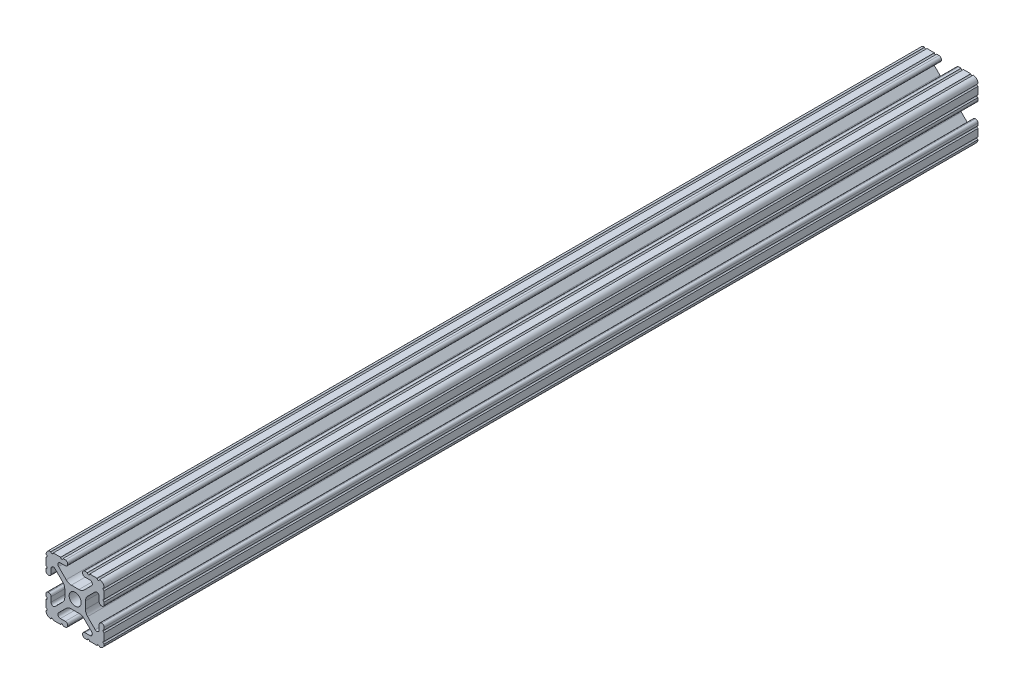
SolidWorks part; units mm, degrees
ref_plane "Front Plane" through (0, 0, 0) normal (0, 0, 1) x (1, 0, 0)
ref_plane "Top Plane" through (0, 0, 0) normal (0, 1, 0) x (1, 0, 0)
ref_plane "Right Plane" through (0, 0, 0) normal (1, 0, 0) x (0, 0, -1)
sketch "Sketch1" plane through (0, 0, 0) normal (0, 0, 1) x (1, 0, 0)
  line L88 (-7.1797, -8.6452) -> (-3.9523, -5.4237)
  line L89 (-1.7093, -4.4958) -> (1.7093, -4.4958)
  line L90 (3.9523, -5.4237) -> (7.1797, -8.6452)
  line L91 (6.4164, -10.4902) -> (4.2875, -10.4902)
  line L92 (3.2385, -11.5392) -> (3.2385, -11.651)
  line L93 (4.2875, -12.7) -> (5.3171, -12.7)
  line L94 (6.3331, -12.7) -> (9.5504, -12.7)
  line L95 (12.7, -9.5504) -> (12.7, -6.3331)
  line L96 (12.7, -5.3171) -> (12.7, -4.2875)
  line L97 (11.651, -3.2385) -> (11.5392, -3.2385)
  line L98 (10.4902, -4.2875) -> (10.4902, -6.4021)
  line L99 (8.7371, -7.1294) -> (5.441, -3.8408)
  line L100 (4.5085, -1.5932) -> (4.5085, 1.5932)
  line L101 (5.441, 3.8408) -> (8.7371, 7.1294)
  line L102 (10.4902, 6.4021) -> (10.4902, 4.2875)
  line L103 (11.5392, 3.2385) -> (11.651, 3.2385)
  line L104 (12.7, 4.2875) -> (12.7, 5.3171)
  line L105 (12.7, 6.3331) -> (12.7, 9.5504)
  line L106 (9.5504, 12.7) -> (6.3331, 12.7)
  line L107 (5.3171, 12.7) -> (4.2875, 12.7)
  line L108 (3.2385, 11.651) -> (3.2385, 11.5392)
  line L109 (4.2875, 10.4902) -> (6.4768, 10.4902)
  line L110 (7.207, 8.7244) -> (3.8983, 5.4232)
  line L111 (1.6558, 4.4958) -> (-1.6558, 4.4958)
  line L112 (-3.8983, 5.4232) -> (-7.207, 8.7244)
  line L113 (-6.4768, 10.4902) -> (-4.2875, 10.4902)
  line L114 (-3.2385, 11.5392) -> (-3.2385, 11.651)
  line L115 (-4.2875, 12.7) -> (-5.3171, 12.7)
  line L116 (-6.3331, 12.7) -> (-9.5504, 12.7)
  line L117 (-12.7, 9.5504) -> (-12.7, 6.3331)
  line L118 (-12.7, 5.3171) -> (-12.7, 4.2875)
  line L119 (-11.651, 3.2385) -> (-11.5392, 3.2385)
  line L120 (-10.4902, 4.2875) -> (-10.4902, 6.4021)
  line L121 (-8.7371, 7.1294) -> (-5.441, 3.8408)
  line L122 (-4.5085, 1.5932) -> (-4.5085, -1.5932)
  line L123 (-5.441, -3.8408) -> (-8.7371, -7.1294)
  line L124 (-10.4902, -6.4021) -> (-10.4902, -4.2875)
  line L125 (-11.5392, -3.2385) -> (-11.651, -3.2385)
  line L126 (-12.7, -4.2875) -> (-12.7, -5.3171)
  line L127 (-12.7, -6.3331) -> (-12.7, -9.5504)
  line L128 (-9.5504, -12.7) -> (-6.3331, -12.7)
  line L129 (-5.3171, -12.7) -> (-4.2875, -12.7)
  line L130 (-3.2385, -11.651) -> (-3.2385, -11.5392)
  line L131 (-4.2875, -10.4902) -> (-6.4164, -10.4902)
  circle A1 centre (0, 0) radius 2.6035
  arc A104 (-7.1797, -8.6452) -> (-6.4164, -10.4902) centre (-6.4164, -9.4098) ccw
  arc A105 (-1.7093, -4.4958) -> (-3.9523, -5.4237) centre (-1.7093, -7.6708) ccw
  arc A106 (3.9523, -5.4237) -> (1.7093, -4.4958) centre (1.7093, -7.6708) ccw
  arc A107 (6.4164, -10.4902) -> (7.1797, -8.6452) centre (6.4164, -9.4098) ccw
  arc A108 (4.2875, -10.4902) -> (3.2385, -11.5392) centre (4.2875, -11.5392) ccw
  arc A109 (3.2385, -11.651) -> (4.2875, -12.7) centre (4.2875, -11.651) ccw
  arc A110 (6.3331, -12.7) -> (5.3171, -12.7) centre (5.8251, -12.7) ccw
  arc A111 (10.5664, -12.6998) -> (9.5504, -12.7) centre (10.0584, -12.7) ccw
  arc A112 (10.5664, -12.6998) -> (12.6998, -10.5664) centre (10.5918, -10.5918) ccw
  arc A113 (12.7, -9.5504) -> (12.6998, -10.5664) centre (12.7, -10.0584) ccw
  arc A114 (12.7, -5.3171) -> (12.7, -6.3331) centre (12.7, -5.8251) ccw
  arc A115 (12.7, -4.2875) -> (11.651, -3.2385) centre (11.651, -4.2875) ccw
  arc A116 (11.5392, -3.2385) -> (10.4902, -4.2875) centre (11.5392, -4.2875) ccw
  arc A117 (8.7371, -7.1294) -> (10.4902, -6.4021) centre (9.4628, -6.4021) ccw
  arc A118 (4.5085, -1.5932) -> (5.441, -3.8408) centre (7.6835, -1.5932) ccw
  arc A119 (5.441, 3.8408) -> (4.5085, 1.5932) centre (7.6835, 1.5932) ccw
  arc A120 (10.4902, 6.4021) -> (8.7371, 7.1294) centre (9.4628, 6.4021) ccw
  arc A121 (10.4902, 4.2875) -> (11.5392, 3.2385) centre (11.5392, 4.2875) ccw
  arc A122 (11.651, 3.2385) -> (12.7, 4.2875) centre (11.651, 4.2875) ccw
  arc A123 (12.7, 6.3331) -> (12.7, 5.3171) centre (12.7, 5.8251) ccw
  arc A124 (12.6998, 10.5664) -> (12.7, 9.5504) centre (12.7, 10.0584) ccw
  arc A125 (12.6998, 10.5664) -> (10.5664, 12.6998) centre (10.5918, 10.5918) ccw
  arc A126 (9.5504, 12.7) -> (10.5664, 12.6998) centre (10.0584, 12.7) ccw
  arc A127 (5.3171, 12.7) -> (6.3331, 12.7) centre (5.8251, 12.7) ccw
  arc A128 (4.2875, 12.7) -> (3.2385, 11.651) centre (4.2875, 11.651) ccw
  arc A129 (3.2385, 11.5392) -> (4.2875, 10.4902) centre (4.2875, 11.5392) ccw
  arc A130 (7.207, 8.7244) -> (6.4768, 10.4902) centre (6.4768, 9.4563) ccw
  arc A131 (1.6558, 4.4958) -> (3.8983, 5.4232) centre (1.6558, 7.6708) ccw
  arc A132 (-3.8983, 5.4232) -> (-1.6558, 4.4958) centre (-1.6558, 7.6708) ccw
  arc A133 (-6.4768, 10.4902) -> (-7.207, 8.7244) centre (-6.4768, 9.4563) ccw
  arc A134 (-4.2875, 10.4902) -> (-3.2385, 11.5392) centre (-4.2875, 11.5392) ccw
  arc A135 (-3.2385, 11.651) -> (-4.2875, 12.7) centre (-4.2875, 11.651) ccw
  arc A136 (-6.3331, 12.7) -> (-5.3171, 12.7) centre (-5.8251, 12.7) ccw
  arc A137 (-10.5664, 12.6998) -> (-9.5504, 12.7) centre (-10.0584, 12.7) ccw
  arc A138 (-10.5664, 12.6998) -> (-12.6998, 10.5664) centre (-10.5918, 10.5918) ccw
  arc A139 (-12.7, 9.5504) -> (-12.6998, 10.5664) centre (-12.7, 10.0584) ccw
  arc A140 (-12.7, 5.3171) -> (-12.7, 6.3331) centre (-12.7, 5.8251) ccw
  arc A141 (-12.7, 4.2875) -> (-11.651, 3.2385) centre (-11.651, 4.2875) ccw
  arc A142 (-11.5392, 3.2385) -> (-10.4902, 4.2875) centre (-11.5392, 4.2875) ccw
  arc A143 (-8.7371, 7.1294) -> (-10.4902, 6.4021) centre (-9.4628, 6.4021) ccw
  arc A144 (-4.5085, 1.5932) -> (-5.441, 3.8408) centre (-7.6835, 1.5932) ccw
  arc A145 (-5.441, -3.8408) -> (-4.5085, -1.5932) centre (-7.6835, -1.5932) ccw
  arc A146 (-10.4902, -6.4021) -> (-8.7371, -7.1294) centre (-9.4628, -6.4021) ccw
  arc A147 (-10.4902, -4.2875) -> (-11.5392, -3.2385) centre (-11.5392, -4.2875) ccw
  arc A148 (-11.651, -3.2385) -> (-12.7, -4.2875) centre (-11.651, -4.2875) ccw
  arc A149 (-12.7, -6.3331) -> (-12.7, -5.3171) centre (-12.7, -5.8251) ccw
  arc A150 (-12.6998, -10.5664) -> (-12.7, -9.5504) centre (-12.7, -10.0584) ccw
  arc A151 (-12.6998, -10.5664) -> (-10.5664, -12.6998) centre (-10.5918, -10.5918) ccw
  arc A152 (-9.5504, -12.7) -> (-10.5664, -12.6998) centre (-10.0584, -12.7) ccw
  arc A153 (-5.3171, -12.7) -> (-6.3331, -12.7) centre (-5.8251, -12.7) ccw
  arc A154 (-4.2875, -12.7) -> (-3.2385, -11.651) centre (-4.2875, -11.651) ccw
  arc A155 (-3.2385, -11.5392) -> (-4.2875, -10.4902) centre (-4.2875, -11.5392) ccw
extrude "Boss-Extrude1" add sketch "Sketch1" along normal mid plane 609.6
sketch "Sketch2" plane through (0, 0, 304.8) normal (0, 0, 1) x (1, 0, 0)
  line L1 (-89.9579, 50.7588) -> (108.4825, 50.7588)
  line L2 (-89.9579, 50.7588) -> (-89.9579, -76.9578)
  line L3 (-89.9579, -76.9578) -> (108.4825, -76.9578)
  line L4 (108.4825, 50.7588) -> (108.4825, -76.9578)
extrude "Cut-Extrude1" cut sketch "Sketch2" against normal blind 228.6
